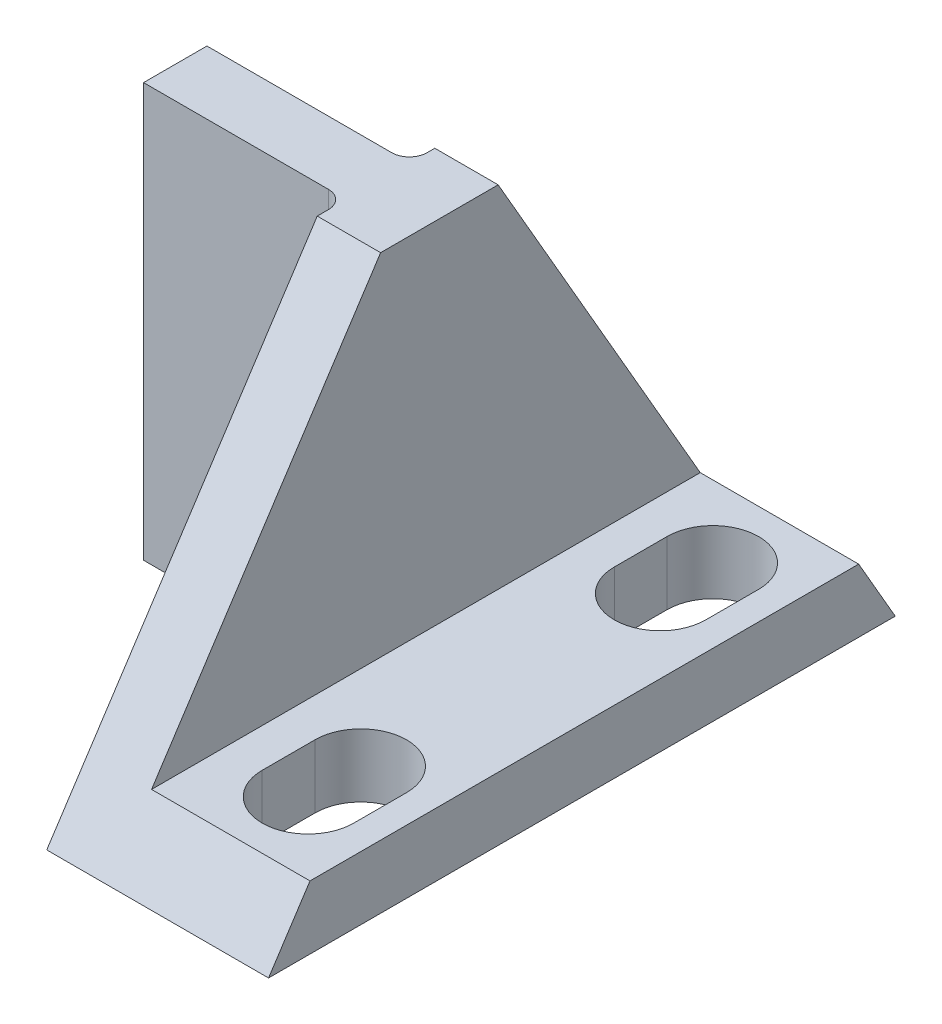
SolidWorks part; units mm, degrees
ref_plane "Front Plane" through (0, 0, 0) normal (0, 0, 1) x (1, 0, 0)
ref_plane "Top Plane" through (0, 0, 0) normal (0, 1, 0) x (1, 0, 0)
ref_plane "Right Plane" through (0, 0, 0) normal (1, 0, 0) x (0, 0, -1)
sketch "Sketch1" plane through (0, 0, 0) normal (0, 0, 1) x (1, 0, 0)
  line L1 (0, 0) -> (14.605, 0)
  line L2 (0, 0) -> (0, 33.02)
  line L3 (0, 33.02) -> (14.605, 33.02)
  line L4 (14.605, 0) -> (14.605, 33.02)
  dimension "D1" = 14.605
  dimension "D2" = 33.02
extrude "Boss-Extrude1" add sketch "Sketch1" along normal blind 4.572
sketch "Sketch2" plane through (14.605, 0, 0) normal (1, 0, 0) x (0, 0, -1)
  line L0 (-4.572, 33.02) -> (-26.162, 0)
  line L1 (-26.162, 0) -> (19.05, 0)
  line L2 (19.05, 0) -> (0, 33.02)
  line L3 (-4.572, 33.02) -> (0, 33.02)
  line L4 (-4.572, 0) -> (-4.572, 33.02) construction
  line L5 (0, 0) -> (0, 33.02) construction
  dimension "D1" = 21.59
  dimension "D2" = 19.05
extrude "Boss-Extrude2" add sketch "Sketch2" along normal blind 4.572
sketch "Sketch3" plane through (19.177, 0, 0) normal (1, 0, 0) x (0, 0, -1)
  line L0 (-23.1726, 4.572) -> (16.4123, 4.572)
  line L1 (-4.572, 33.02) -> (-26.162, 0) construction
  line L2 (19.05, 0) -> (0, 33.02) construction
  line L3 (16.4123, 4.572) -> (19.05, 0)
  line L4 (19.05, 0) -> (-26.162, 0)
  line L5 (-26.162, 0) -> (-23.1726, 4.572)
  dimension "D1" = 4.572
extrude "Boss-Extrude3" add sketch "Sketch3" along normal blind 11.43
sketch "Sketch4" plane through (0, 4.572, 0) normal (0, 1, 0) x (1, 0, 0)
  line L0 (25.273, 11.2248) -> (25.273, 7.4148) construction
  line L1 (28.575, 11.2248) -> (28.575, 7.4148)
  line L2 (21.971, 11.2248) -> (21.971, 7.4148)
  line L3 (25.273, -14.1752) -> (25.273, -17.9852) construction
  line L4 (28.575, -14.1752) -> (28.575, -17.9852)
  line L5 (21.971, -14.1752) -> (21.971, -17.9852)
  line L6 (19.177, 16.4123) -> (19.177, -23.1726) construction
  line L7 (19.177, -4.572) -> (19.177, -23.1726) construction
  line L8 (30.607, -3.3802) -> (3.3099, -3.3802) construction
  line L10 (30.607, 16.4123) -> (30.607, -23.1726) construction
  arc A0 (28.575, 11.2248) -> (21.971, 11.2248) centre (25.273, 11.2248) ccw
  arc A1 (21.971, 7.4148) -> (28.575, 7.4148) centre (25.273, 7.4148) ccw
  arc A2 (28.575, -14.1752) -> (21.971, -14.1752) centre (25.273, -14.1752) ccw
  arc A3 (21.971, -17.9852) -> (28.575, -17.9852) centre (25.273, -17.9852) ccw
  point P2 (25.273, 9.3198)
  point P7 (25.273, -16.0802)
  dimension "D1" = 3.302
  dimension "D3" = 3.302
  dimension "D2" = 6.096
  dimension "D4" = 6.096
  dimension "D5" = 12.7
  dimension "D6" = 12.7
  dimension "D7" = 3.81
  dimension "D8" = 3.81
extrude "Cut-Extrude1" cut sketch "Sketch4" against normal through all
sketch "Sketch5" plane through (0, 0, 0) normal (-1, 0, 0) x (0, 0, 1)
  line L1 (0, 20.32) -> (4.572, 20.32) construction
  line L2 (0, 0) -> (0, 33.02) construction
  line L3 (4.572, 33.02) -> (4.572, 0) construction
  line L4 (2.286, 12.72) -> (2.286, 39.846) construction
  line L5 (4.572, 0) -> (0, 0) construction
  circle A0 centre (2.286, 26.67) radius 1.25
  circle A1 centre (2.286, 13.97) radius 1.25
  dimension "D2" = 2.5
  dimension "D3" = 2.5
  dimension "D1" = 20.32
  dimension "D4" = 6.35
  dimension "D5" = 6.35
extrude "Cut-Extrude2" cut sketch "Sketch5" against normal blind 11.43
sketch "Sketch6" plane through (0, 33.02, 0) normal (0, 1, 0) x (1, 0, 0)
  line L1 (0, 6.0399) -> (33.3557, 6.0399)
  line L2 (0, 6.0399) -> (0, -12.792)
  line L3 (0, -12.792) -> (33.3557, -12.792)
  line L4 (33.3557, 6.0399) -> (33.3557, -12.792)
extrude "Cut-Extrude3" cut sketch "Sketch6" against normal blind 3.175
fillet "Fillet1" radius 1.27 2 edges at (14.605, 14.9225, 4.572) (14.605, 14.9225, 0)
